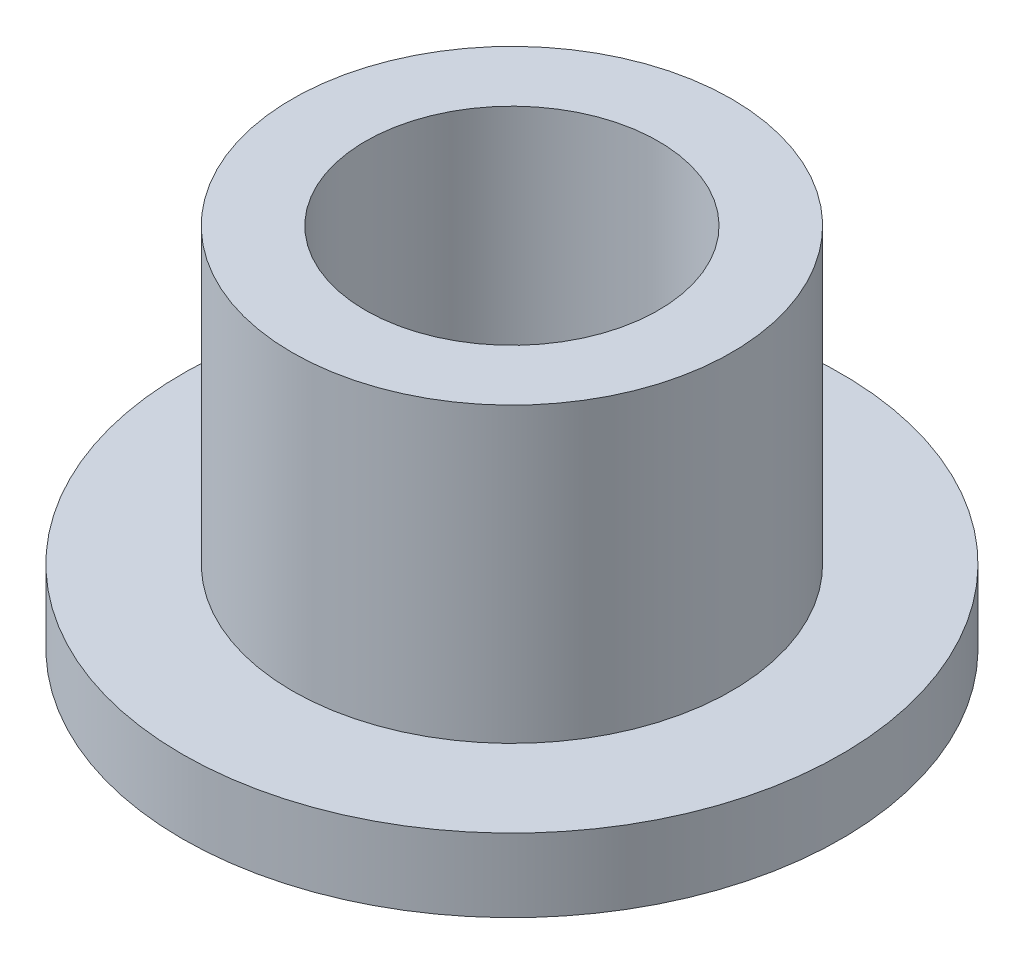
SolidWorks part; units mm, degrees
ref_plane "Front Plane" through (0, 0, 0) normal (0, 0, 1) x (1, 0, 0)
ref_plane "Top Plane" through (0, 0, 0) normal (0, 1, 0) x (1, 0, 0)
ref_plane "Right Plane" through (0, 0, 0) normal (1, 0, 0) x (0, 0, -1)
sketch "Sketch1" plane through (0, 0, 0) normal (0, 1, 0) x (1, 0, 0)
  circle A0 centre (0, 0) radius 14.2875
  dimension "D1" = 28.575
extrude "Boss-Extrude1" add sketch "Sketch1" along normal blind 3.175
sketch "Sketch2" plane through (0, 3.175, 0) normal (0, 1, 0) x (1, 0, 0)
  circle A0 centre (0, 0) radius 9.525
  circle A1 centre (0, 0) radius 6.35
  dimension "D1" = 19.05
  dimension "D2" = 12.7
extrude "Boss-Extrude2" add sketch "Sketch2" along normal blind 12.7
